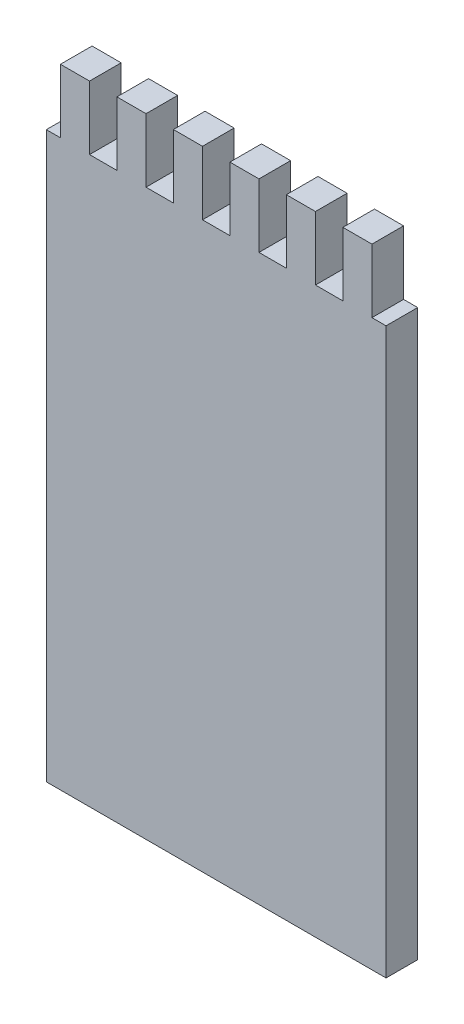
SolidWorks part; units mm, degrees
ref_plane "Piano frontale" through (0, 0, 0) normal (0, 0, 1) x (1, 0, 0)
ref_plane "Piano superiore" through (0, 0, 0) normal (0, 1, 0) x (1, 0, 0)
ref_plane "Piano destro" through (0, 0, 0) normal (1, 0, 0) x (0, 0, -1)
sketch "Schizzo1" plane through (0, 0, 0) normal (0, 0, 1) x (1, 0, 0)
  line L0 (-17.575, 55.875) -> (-12.425, 55.875)
  line L1 (-27.575, -55.4) -> (27.575, -55.4)
  line L3 (-22.425, 44.6) -> (-17.575, 44.6)
  line L5 (0, 67.1499) -> (0, -65.4713) construction
  line L6 (-27.575, 44.6) -> (-30.075, 44.6)
  line L7 (-12.425, 44.6) -> (-7.575, 44.6)
  line L8 (-27.575, 44.6) -> (-27.575, 55.875)
  line L9 (-27.575, 55.875) -> (-22.425, 55.875)
  line L10 (-22.425, 44.6) -> (-22.425, 55.875)
  line L11 (-27.575, 44.6) -> (-22.425, 55.875) construction
  line L12 (-27.575, 55.875) -> (-22.425, 44.6) construction
  line L13 (-12.425, 44.6) -> (-12.425, 55.875)
  line L14 (-17.575, 44.6) -> (-17.575, 55.875)
  line L15 (-7.575, 55.875) -> (-2.425, 55.875)
  line L16 (-2.425, 44.6) -> (-2.425, 55.875)
  line L17 (-7.575, 44.6) -> (-7.575, 55.875)
  line L18 (2.425, 55.875) -> (7.575, 55.875)
  line L19 (7.575, 44.6) -> (7.575, 55.875)
  line L20 (2.425, 44.6) -> (2.425, 55.875)
  line L21 (12.425, 55.875) -> (17.575, 55.875)
  line L22 (17.575, 44.6) -> (17.575, 55.875)
  line L23 (12.425, 44.6) -> (12.425, 55.875)
  line L24 (22.425, 55.875) -> (27.575, 55.875)
  line L25 (27.575, 44.6) -> (27.575, 55.875)
  line L26 (22.425, 44.6) -> (22.425, 55.875)
  line L27 (-2.425, 44.6) -> (2.425, 44.6)
  line L28 (7.575, 44.6) -> (12.425, 44.6)
  line L29 (17.575, 44.6) -> (22.425, 44.6)
  line L31 (-27.575, -55.4) -> (-30.075, -55.4)
  line L32 (-30.075, 44.6) -> (-30.075, -55.4)
  line L33 (27.575, -55.4) -> (30.075, -55.4)
  line L34 (27.575, 44.6) -> (30.075, 44.6)
  line L35 (30.075, 44.6) -> (30.075, -55.4)
  point P0 (0, 0)
  point P6 (-25, 50.2375)
  dimension "D2" = 100
  dimension "D3" = 5.15
  dimension "D4" = 11.275
  dimension "D6" = 4.85
  dimension "D1" = 2.5
  dimension "D5" = 6
extrude "Estrusione-Estrusione1" add sketch "Schizzo1" along normal blind 5.6
equation "\"side\"= 65'hexagon side"
equation "\"joint whidth\"= 5"
equation "\"mat thickness\"= 5.6"
equation "\"kerf\"= 0.075"
equation "\"D4@Schizzo1\"= ( \"mat thickness\" * 2 ) + \"kerf\""
equation "\"D3@Schizzo1\"= \"joint whidth\" + ( \"kerf\" * 2 )"
equation "\"D6@Schizzo1\"= \"joint whidth\" - ( \"kerf\" * 2 )"
equation "\"D1@Schizzo1\"= \"joint whidth\" / 2"
